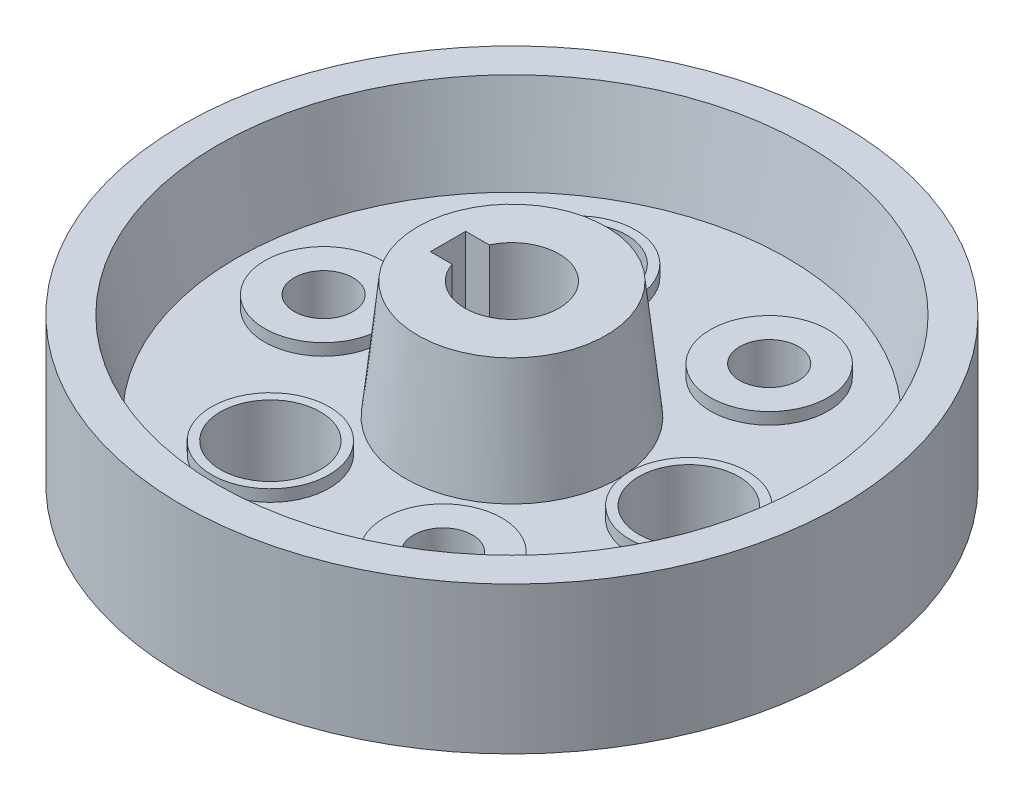
SolidWorks part; units mm, degrees
material "Ferro fundido cinza"
ref_plane "Plano frontal" through (0, 0, 0) normal (0, 0, 1) x (1, 0, 0)
ref_plane "Plano superior" through (0, 0, 0) normal (0, 1, 0) x (1, 0, 0)
ref_plane "Plano direito" through (0, 0, 0) normal (1, 0, 0) x (0, 0, -1)
sketch "Esboço1" plane through (0, 0, 0) normal (0, 0, 1) x (1, 0, 0)
  line L0 (0, 0) -> (48, 0)
  line L1 (0, 0) -> (0, 25)
  line L2 (0, 25) -> (6, 25)
  line L5 (6, 25) -> (9.2235, 10)
  line L6 (9.2235, 10) -> (14.2235, 10)
  line L10 (32.8667, 10) -> (37.8667, 10)
  line L11 (37.8667, 10) -> (40, 30)
  line L12 (40, 30) -> (48, 30)
  line L20 (48, 30) -> (48, 0)
  line L21 (56, 30) -> (56, 0) construction
  line L22 (14.2235, 10) -> (32.8667, 10)
  dimension "D1" = 56
  dimension "D2" = 30
  dimension "D3" = 16
  dimension "D4" = 10
  dimension "D5" = 10
  dimension "D6" = 5
  dimension "D7" = 6
  dimension "D8" = 5
  dimension "D9" = 25
revolve "Revolução1" add sketch "Esboço1" angle 360 about L21
sketch "Esboço2" plane through (0, 10, 0) normal (0, 1, 0) x (1, 0, 0)
  circle A0 centre (24, 0) radius 5
  circle A1 centre (56, 0) radius 8 construction
  point P2 (0, 0)
  point P5 (23, 0)
  dimension "D1" = 10
  dimension "D2" = 32
extrude "Corte-extrusão2" cut sketch "Esboço2" against normal blind 30
pattern_circular "PadrãoCircular1" count 3 over 360 about axis through (56, 0, 0) along (0, 1, 0) of "Corte-extrusão2"
sketch "Esboço6" plane through (0, 0, 0) normal (0, -1, 0) x (1, 0, 0)
  circle A0 centre (24, 0) radius 6
  dimension "D1" = 12
extrude "Corte-extrusão5" cut sketch "Esboço6" against normal blind 2
pattern_circular "PadrãoCircular4" count 3 over 360 about axis through (56, 0, 0) along (0, 1, 0) of "Corte-extrusão5"
sketch "Esboço9" plane through (0, 30, 0) normal (0, 1, 0) x (1, 0, 0)
  line L1 (48.7545, 3.3915) -> (44.7562, 3.3915)
  line L2 (48.7545, 3.3915) -> (48.7545, -2.6085)
  line L3 (48.7545, -2.6085) -> (44.7562, -2.6085)
  line L4 (44.7562, 3.3915) -> (44.7562, -2.6085)
  circle A0 centre (56, 0) radius 8 construction
  dimension "D1" = 6
extrude "Corte-extrusão6" cut sketch "Esboço9" against normal through all
sketch "Esboço10" plane through (0, 10, 0) normal (0, 1, 0) x (1, 0, 0)
  line L0 (56, 0) -> (40.9773, 26.0201) construction
  line L1 (40.9773, 26.0201) -> (24, 0) construction
  line L2 (24, 0) -> (56, 0) construction
  circle A0 centre (40.9773, 26.0201) radius 8.5
  dimension "D1" = 60
  dimension "D2" = 17
extrude "Corte-extrusão7" cut sketch "Esboço10" against normal blind 10
pattern_circular "PadrãoCircular5" count 3 over 360 about axis through (56, 0, 0) along (0, 1, 0) of "Corte-extrusão7"
sketch "Esboço11" plane through (0, 10, 0) normal (0, 1, 0) x (1, 0, 0)
  circle A0 centre (40.9773, 26.0201) radius 10
  circle A1 centre (86.0454, 0) radius 10
  circle A2 centre (40.9773, -26.0201) radius 10
  dimension "D1" = 20
  dimension "D2" = 20
  dimension "D3" = 20
extrude "Ressalto-extrusão1" add sketch "Esboço11" along normal blind 2
sketch "Esboço12" plane through (0, 10, 0) normal (0, 1, 0) x (1, 0, 0)
  circle A0 centre (40.9773, 26.0201) radius 8.5
  circle A1 centre (40.9773, -26.0201) radius 8.5
  circle A2 centre (86.0454, 0) radius 8.5
  dimension "D1" = 17
  dimension "D2" = 17
  dimension "D3" = 17
extrude "Corte-extrusão9" cut sketch "Esboço12" along normal blind 2
sketch "Esboço13" plane through (0, 10, 0) normal (0, 1, 0) x (1, 0, 0)
  circle A0 centre (24, 0) radius 10
  circle A1 centre (24, 0) radius 5
  dimension "D1" = 20
extrude "Ressalto-extrusão2" add sketch "Esboço13" along normal blind 2
pattern_circular "PadrãoCircular6" count 3 over 360 about axis through (56, 0, 0) along (0, 1, 0) of "Ressalto-extrusão2", "Corte-extrusão2"
sketch "Esboço14" plane through (0, 0, 0) normal (0, -1, 0) x (1, 0, 0)
  circle A0 centre (56, 0) radius 17.5
  dimension "D1" = 35
extrude "Corte-extrusão10" cut sketch "Esboço14" against normal blind 3
